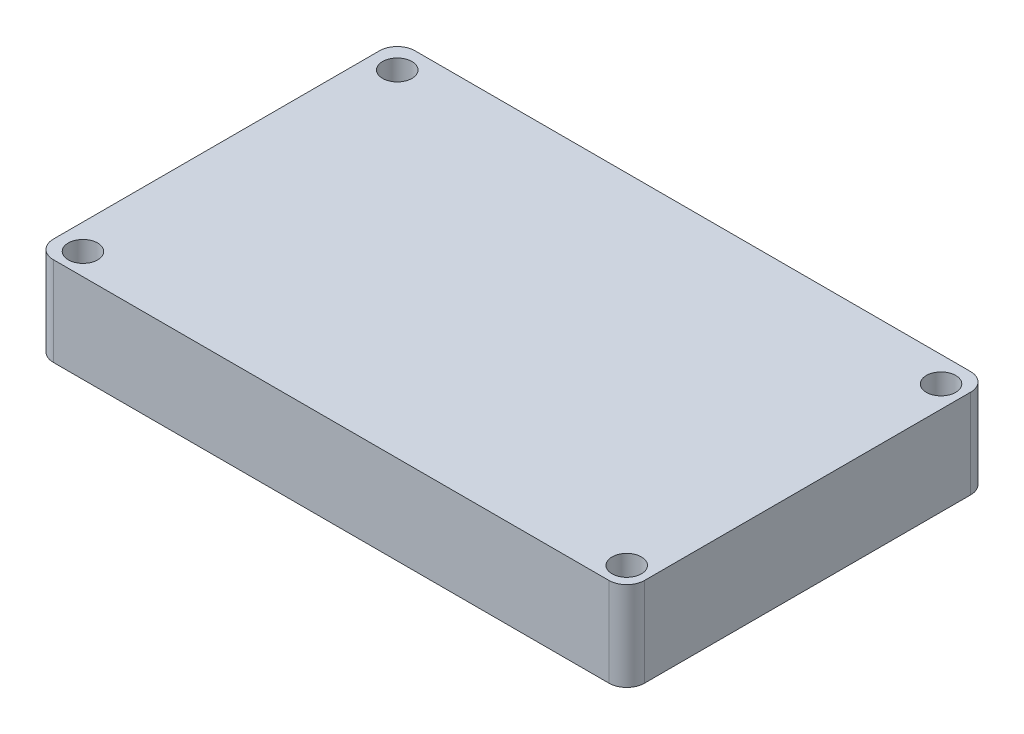
SolidWorks part; units mm, degrees
ref_plane "Front Plane" through (0, 0, 0) normal (0, 0, 1) x (1, 0, 0)
ref_plane "Top Plane" through (0, 0, 0) normal (0, 1, 0) x (1, 0, 0)
ref_plane "Right Plane" through (0, 0, 0) normal (1, 0, 0) x (0, 0, -1)
sketch "Sketch1" plane through (0, 0, 0) normal (0, 1, 0) x (1, 0, 0)
  line L1 (0, 0) -> (66.42, 0)
  line L2 (0, 0) -> (0, 40.64)
  line L3 (0, 40.64) -> (66.42, 40.64)
  line L4 (66.42, 0) -> (66.42, 40.64)
  dimension "D1" = 40.64
  dimension "D2" = 66.42
extrude "Boss-Extrude1" add sketch "Sketch1" along normal blind 10
sketch "Sketch2" plane through (0, 10, 0) normal (0, 1, 0) x (1, 0, 0)
  line L0 (66.42, 0) -> (66.42, 40.64) construction
  line L1 (0, 0) -> (66.42, 0) construction
  circle A0 centre (63.955, 2.465) radius 1.65
  circle A1 centre (63.955, 37.775) radius 1.65
  circle A2 centre (2.865, 37.775) radius 1.65
  circle A3 centre (2.865, 2.465) radius 1.65
  dimension "D4" = 3.3
  dimension "D1" = 35.31
  dimension "D2" = 2.465
  dimension "D3" = 61.09
  dimension "D5" = 2.465
extrude "Cut-Extrude1" cut sketch "Sketch2" against normal up to surface (10 mm away) up to face at (33.21, 0, -20.32)
fillet "Fillet1" radius 2 4 edges at (0, 5, 0) (0, 5, -40.64) (66.42, 5, -40.64) (66.42, 5, 0)
